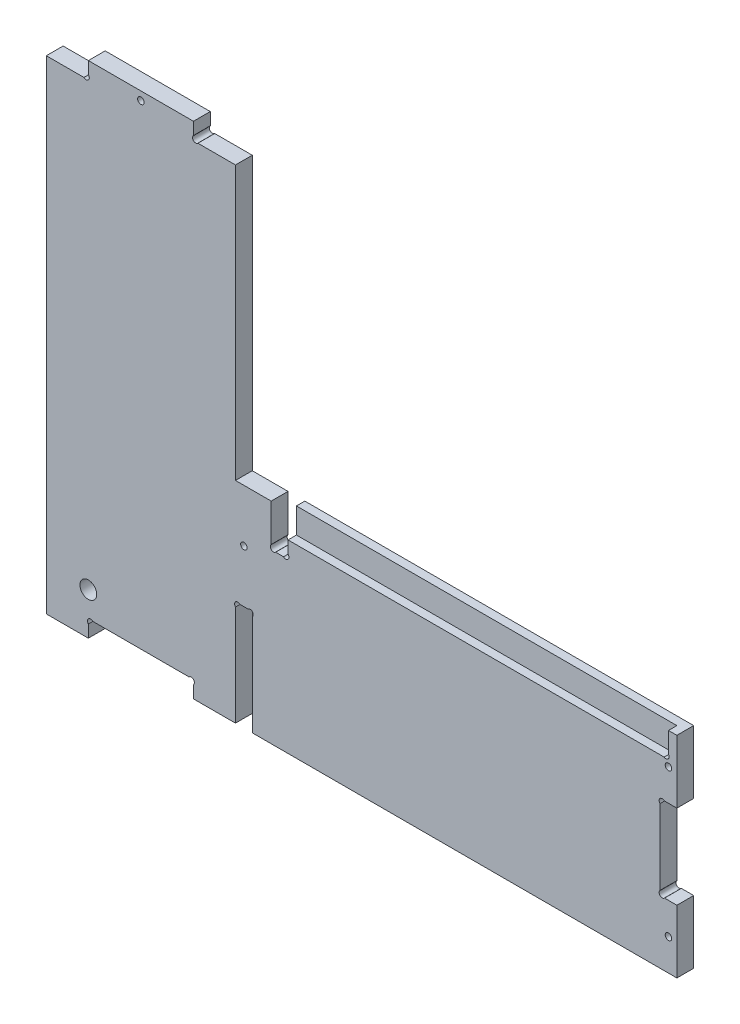
SolidWorks part; units mm, degrees
ref_plane "Plan de face" through (0, 0, 0) normal (0, 0, 1) x (1, 0, 0)
ref_plane "Plan de dessus" through (0, 0, 0) normal (0, 1, 0) x (1, 0, 0)
ref_plane "Plan de droite" through (0, 0, 0) normal (1, 0, 0) x (0, 0, -1)
sketch "Esquisse1" plane through (0, 0, 0) normal (0, 0, 1) x (1, 0, 0)
  line L0 (-40.0343, 75.0386) -> (47.9648, 75.0386) construction
  line L1 (43.9657, 14.0749) -> (43.9657, 64.0749) construction
  line L2 (-50.0352, 24.0585) -> (-50.0352, -35.9251)
  line L3 (-50.0352, -35.9251) -> (-30.0352, -35.9251)
  line L4 (249.9648, 64.0749) -> (249.9648, 34.0585)
  line L5 (47.9648, -34.0836) -> (47.9648, 93.7119) construction
  line L6 (47.9648, -35.9251) -> (47.9648, 11.9363)
  line L7 (42.0704, 14.0749) -> (45.861, 14.0749)
  line L8 (39.9648, -35.9251) -> (39.9648, 11.9381)
  line L9 (47.9648, -35.9251) -> (249.9648, -35.9251)
  line L10 (245.9648, 75.0386) -> (60.9648, 75.0386) construction
  line L11 (39.9648, -35.9251) -> (39.9648, 202.0749) construction
  line L12 (22.0861, 194.0749) -> (39.9648, 194.0749)
  line L13 (245.9648, -38.4602) -> (245.9648, 75.0386) construction
  line L14 (60.9648, 91.8154) -> (60.9648, -35.9801) construction
  line L15 (56.9648, 64.0749) -> (56.9648, 46.1953)
  line L16 (59.087, 44.0749) -> (62.8436, 44.0749)
  line L17 (64.9648, 46.1962) -> (64.9648, 64.0749)
  line L18 (64.9648, 64.0749) -> (249.9648, 64.0749)
  line L19 (283.5481, 14.0585) -> (224.3033, 14.0585) construction
  line L20 (241.9648, -3.821) -> (241.9648, 31.9372)
  line L21 (244.0861, 34.0585) -> (249.9648, 34.0585)
  line L22 (244.087, -5.9415) -> (249.9648, -5.9415)
  line L23 (249.9648, -5.9415) -> (249.9648, -35.9251)
  line L24 (39.9648, 202.0749) -> (-50.0343, 202.0749) construction
  line L25 (-50.0343, 202.0749) -> (-50.0343, -35.9251) construction
  line L26 (-50.0352, 24.0585) -> (-50.0352, 194.0749)
  line L27 (-52.8991, -27.9251) -> (41.0264, -27.9251) construction
  line L28 (39.9648, 194.0749) -> (39.9648, 64.0749)
  line L29 (19.9648, 202.0749) -> (-30.0352, 202.0749)
  line L30 (-30.0352, 202.0749) -> (-30.0352, 196.1962)
  line L31 (19.9648, 196.1962) -> (19.9648, 202.0749)
  line L32 (-32.1565, 194.0749) -> (-50.0352, 194.0749)
  line L33 (39.9648, 202.0749) -> (39.9648, 194.0749) construction
  line L34 (39.9648, 198.0749) -> (-50.0343, 198.0749) construction
  line L35 (241.9648, 34.0585) -> (249.9648, 64.0749) construction
  line L36 (-30.0352, -35.9251) -> (-30.0352, -30.0464)
  line L37 (39.9648, 64.0749) -> (56.9648, 64.0749)
  line L38 (-27.9139, -27.9251) -> (17.8444, -27.9251)
  line L39 (19.9657, -30.0464) -> (19.9657, -35.9251)
  line L40 (19.9657, -35.9251) -> (39.9648, -35.9251)
  line L41 (249.9648, -35.9251) -> (241.9648, -5.9251) construction
  arc A0 (56.9648, 46.1953) -> (59.087, 44.0749) centre (58.0259, 45.1351) ccw
  arc A1 (62.8436, 44.0749) -> (64.9648, 46.1962) centre (63.9128, 45.127) ccw
  arc A2 (42.0704, 14.0749) -> (39.9648, 11.9381) centre (41.0264, 12.9979) ccw
  arc A3 (47.9648, 11.9363) -> (45.861, 14.0749) centre (46.905, 12.9979) ccw
  arc A4 (244.0861, 34.0585) -> (241.9648, 31.9372) centre (243.0255, 32.9979) ccw
  arc A5 (241.9648, -3.821) -> (244.087, -5.9415) centre (243.0264, -4.8808) ccw
  arc A6 (-32.1565, 194.0749) -> (-30.0352, 196.1962) centre (-31.0958, 195.1355) ccw
  arc A7 (19.9648, 196.1962) -> (22.0861, 194.0749) centre (21.0255, 195.1355) ccw
  circle A8 centre (43.9657, 39.0749) radius 1.55
  circle A9 centre (-5.0347, 198.0749) radius 1.55
  circle A10 centre (245.9648, -20.9251) radius 1.55
  circle A11 centre (245.9648, 49.0667) radius 1.55
  arc A12 (-27.9139, -27.9251) -> (-30.0352, -30.0464) centre (-28.9745, -28.9858) ccw
  arc A13 (19.9657, -30.0464) -> (17.8444, -27.9251) centre (18.905, -28.9858) ccw
  point P30 (251.9657, 14.0585)
  dimension "D5" = 8
  dimension "D7" = 1.5
  dimension "D8" = 1.5
  dimension "D11" = 1.5
  dimension "D12" = 1.5
  dimension "D14" = 300
  dimension "D15" = 1.5
  dimension "D2" = 8
  dimension "D18" = 4
  dimension "D1" = 4
  dimension "D3" = 185
  dimension "D4" = 100
  dimension "D6" = 5.8787
  dimension "D9" = 8
  dimension "D10" = 90
  dimension "D13" = 50
  dimension "D16" = 20
  dimension "D17" = 17.8787
  dimension "D19" = 20
  dimension "D20" = 8
  dimension "D22" = 20
extrude "Boss.-Extru.1" add sketch "Esquisse1" along normal blind 8
sketch "Esquisse2" plane through (0, 0, 8) normal (0, 0, 1) x (1, 0, 0)
  line L0 (60.9648, 52.0749) -> (243.8984, 52.0749)
  line L1 (249.9648, 34.0585) -> (249.9648, 64.0749) construction
  line L2 (245.9648, 54.1962) -> (245.9648, 64.0749)
  line L4 (60.9648, 52.0749) -> (60.9648, 64.0749)
  line L5 (249.9648, 64.0749) -> (64.9648, 64.0749) construction
  line L6 (245.9648, 64.0749) -> (60.9648, 64.0749)
  line L7 (56.9648, 46.1953) -> (56.9648, 64.0749) construction
  arc A0 (243.8984, 52.0749) -> (245.9648, 54.1962) centre (244.7599, 53.3028) ccw
  dimension "D2" = 4
  dimension "D1" = 4
  dimension "D4" = 12
extrude "Enlèv. mat.-Extru.1" cut sketch "Esquisse2" against normal blind 4
ref_plane "Plan1" through (245.9648, 64.0749, 4) normal (0, 0, 1) x (1, 0, 0)
sketch "Esquisse3" plane through (0, 0, 8) normal (0, 0, 1) x (1, 0, 0)
  line L0 (-30.0352, -35.9251) -> (-30.0352, -15.9251) construction
  line L1 (-50.0352, -35.9251) -> (-30.0352, -35.9251) construction
  line L2 (-50.0352, 194.0749) -> (-50.0352, -35.9251) construction
  circle A0 centre (-30.0352, -15.9251) radius 4
  dimension "D1" = 20
extrude "Enlèv. mat.-Extru.2" cut sketch "Esquisse3" against normal blind 8
